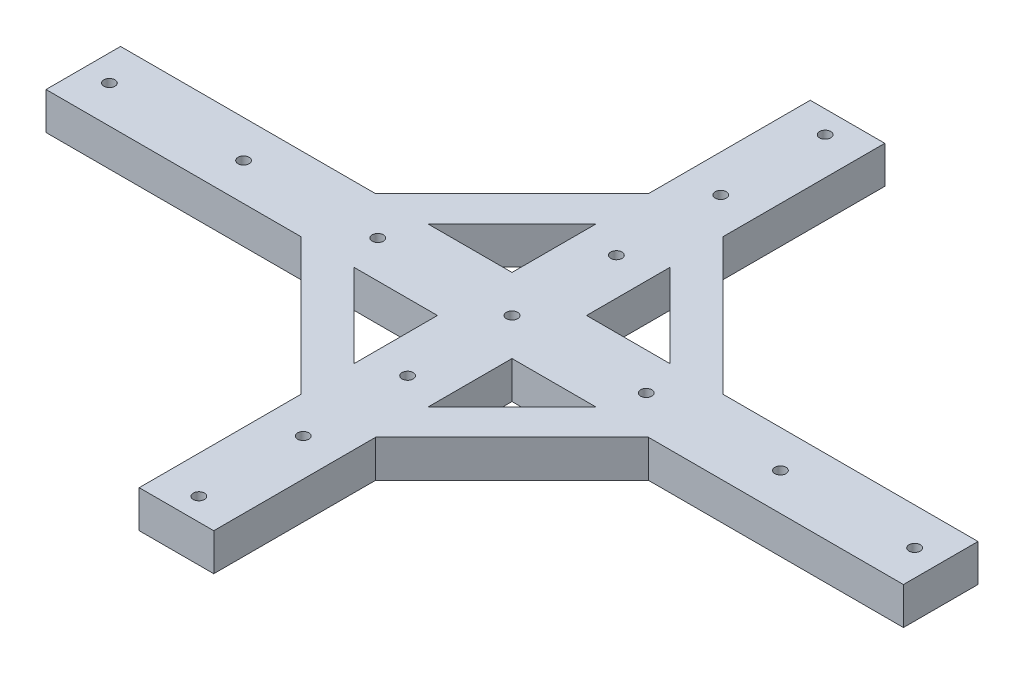
SolidWorks part; units mm, degrees
ref_plane "Front Plane" through (0, 0, 0) normal (0, 0, 1) x (1, 0, 0)
ref_plane "Top Plane" through (0, 0, 0) normal (0, 1, 0) x (1, 0, 0)
ref_plane "Right Plane" through (0, 0, 0) normal (1, 0, 0) x (0, 0, -1)
sketch "Sketch1" plane through (0, 0, 0) normal (0, 1, 0) x (1, 0, 0)
  line L1 (-115, -10) -> (-10, -10)
  line L2 (-115, -10) -> (-115, 10)
  line L3 (-115, 10) -> (-10, 10)
  line L4 (115, -10) -> (115, 10)
  line L5 (-115, -10) -> (115, 10) construction
  line L6 (-115, 10) -> (115, -10) construction
  line L7 (-10, -90) -> (10, -90)
  line L8 (-10, -90) -> (-10, -10)
  line L9 (-10, 90) -> (10, 90)
  line L10 (10, -90) -> (10, -10)
  line L11 (-10, -90) -> (10, 90) construction
  line L12 (-10, 90) -> (10, -90) construction
  line L13 (-10, 10) -> (-10, 90)
  line L14 (10, 10) -> (115, 10)
  line L15 (10, 10) -> (10, 90)
  line L16 (10, -10) -> (115, -10)
  point P0 (0, 0)
  point P6 (0, 0)
  point P13 (0, 0)
  point P14 (0, 0)
  dimension "D1" = 230
  dimension "D2" = 20
  dimension "D3" = 180
extrude "Boss-Extrude1" add sketch "Sketch1" along normal blind 10
sketch "Sketch3" plane through (0, 0, 0) normal (0, 1, 0) x (1, 0, 0)
  line L0 (0, -56.5685) -> (56.5685, 0)
  line L1 (0, -56.5685) -> (-56.5685, 0)
  line L2 (56.5685, 0) -> (0, 56.5685)
  line L3 (-56.5685, 0) -> (0, 56.5685)
  line L4 (0, -56.5685) -> (0, 56.5685) construction
  line L5 (56.5685, 0) -> (-56.5685, 0) construction
  line L6 (0, -42.4264) -> (42.4264, 0)
  line L7 (0, -42.4264) -> (-42.4264, 0)
  line L8 (42.4264, 0) -> (0, 42.4264)
  line L9 (-42.4264, 0) -> (0, 42.4264)
  line L10 (0, -42.4264) -> (0, 42.4264) construction
  line L11 (42.4264, 0) -> (-42.4264, 0) construction
  point P0 (0, 46.9989)
  point P1 (0, 0)
  point P2 (0, 0)
  dimension "D1" = 10
  dimension "D2" = 80
extrude "Boss-Extrude2" add sketch "Sketch3" along normal up to surface (10 mm away) up to face at (0, 10, 0)
sketch "Sketch2" plane through (0, 10, 0) normal (0, 1, 0) x (1, 0, 0)
  line L0 (0, 0) -> (36, 0) construction
  line L1 (0, 0) -> (-36, 0) construction
  line L2 (0, 0) -> (0, 28) construction
  line L3 (0, 0) -> (0, -28) construction
  circle A0 centre (0, 0) radius 1.5
  circle A1 centre (36, 0) radius 1.5
  circle A2 centre (72, 0) radius 1.5
  circle A3 centre (108, 0) radius 1.5
  circle A4 centre (0, 28) radius 1.5
  circle A5 centre (-36, 0) radius 1.5
  circle A6 centre (-72, 0) radius 1.5
  circle A7 centre (-108, 0) radius 1.5
  circle A8 centre (0, 56) radius 1.5
  circle A9 centre (0, 84) radius 1.5
  circle A10 centre (0, -28) radius 1.5
  circle A11 centre (0, -56) radius 1.5
  circle A12 centre (0, -84) radius 1.5
  dimension "D1" = 3
  dimension "D3" = 36
  dimension "D5" = 36
  dimension "D7" = 28
  dimension "D9" = 28
  dimension "D2" = 4
  dimension "D4" = 4
  dimension "D6" = 4
  dimension "D8" = 4
extrude "Cut-Extrude1" cut sketch "Sketch2" against normal through all
